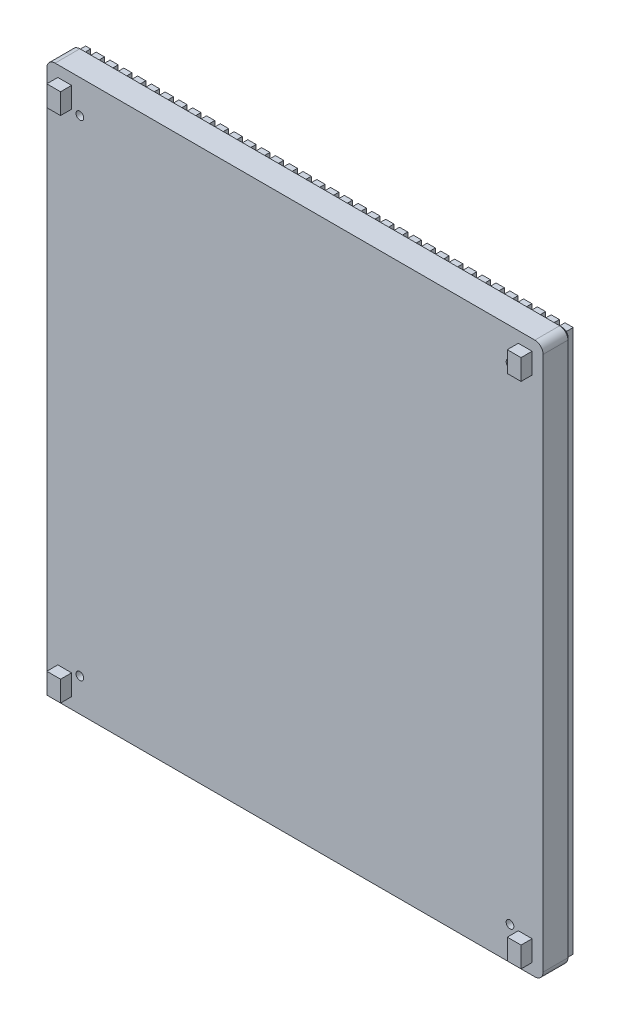
SolidWorks part; units mm, degrees
material "PLA"
ref_plane "Front Plane" through (0, 0, 0) normal (0, 0, 1) x (1, 0, 0)
ref_plane "Top Plane" through (0, 0, 0) normal (0, 1, 0) x (1, 0, 0)
ref_plane "Right Plane" through (0, 0, 0) normal (1, 0, 0) x (0, 0, -1)
sketch "Sketch1" plane through (0, 0, 0) normal (0, 0, 1) x (1, 0, 0)
  line L1 (-180, 200) -> (0, 200)
  line L2 (-180, 200) -> (-180, 0)
  line L3 (-180, 0) -> (0, 0)
  line L4 (0, 200) -> (0, 0)
  circle A0 centre (-168, 188) radius 1.4
  circle A1 centre (-12, 188) radius 1.4
  circle A2 centre (-12, 12) radius 1.4
  circle A3 centre (-168, 12) radius 1.4
  dimension "D3" = 2.8
  dimension "D4" = 2.8
  dimension "D5" = 2.8
  dimension "D6" = 2.8
  dimension "D9" = 12
  dimension "D10" = 12
  dimension "D11" = 12
  dimension "D12" = 12
  dimension "D13" = 12
  dimension "D14" = 12
  dimension "D1" = 200
  dimension "D2" = 180
  dimension "D7" = 12
  dimension "D8" = 12
extrude "Boss-Extrude1" add sketch "Sketch1" along normal blind 10
fillet "Fillet1" radius 3 4 edges at (0, 0, 5) (-180, 0, 5) (-180, 200, 5) (0, 200, 5)
chamfer "Chamfer1" distance 5 angle 40 4 edges at (-10.6, 12, 0) (-166.6, 12, 0) (-166.6, 188, 0) (-10.6, 188, 0)
chamfer "Chamfer2" distance 1 angle 45 8 edges at (-0.8787, 199.1213, 0) (-90, 200, 0) (-179.1213, 199.1213, 0) (-180, 100, 0) (-179.1213, 0.8787, 0) (0, 100, 0) (-0.8787, 0.8787, 0) (-90, 0, 0)
ref_plane "Plane1" through (-90, 0, 0) normal (1, 0, 0) x (0, 0, -1)
sketch "Sketch2" plane through (0, 0, 10) normal (0, 0, 1) x (1, 0, 0)
  line L1 (-176, 196) -> (-171.01, 196)
  line L2 (-176, 196) -> (-176, 188.51)
  line L3 (-176, 188.51) -> (-171.01, 188.51)
  line L4 (-171.01, 196) -> (-171.01, 188.51)
  line L6 (-3, 200) -> (-177, 200) construction
  line L7 (-180, 197) -> (-180, 3) construction
  point P8 (-171.01, 192.255)
  dimension "D1" = 4
  dimension "D2" = 4
  dimension "D3" = 7.49
  dimension "D4" = 4.99
extrude "Boss-Extrude2" add sketch "Sketch2" along normal blind 4
mirror "Mirror1" about plane through (-90, 0, 0) normal (1, 0, 0) of "Boss-Extrude2"
ref_plane "Plane2" through (0, 100, 0) normal (0, 1, 0) x (1, 0, 0)
mirror "Mirror2" about plane through (0, 100, 0) normal (0, 1, 0) of "Mirror1", "Boss-Extrude2"
sketch "Sketch3" plane through (0, 0, 0) normal (0, 0, -1) x (-1, 0, 0)
  line L0 (6.5858, 10.5872) -> (6.5858, 1.5858)
  line L1 (1.5858, 198.4142) -> (4.5858, 198.4142)
  line L2 (1.5858, 198.4142) -> (1.5858, 1.5858)
  line L3 (1.5858, 1.5858) -> (4.5858, 1.5858)
  line L4 (177, 199) -> (3, 199)
  line L5 (1, 197) -> (1, 3)
  line L6 (3, 1) -> (177, 1)
  line L7 (179, 3) -> (179, 197)
  line L8 (177, 199) -> (3, 199)
  line L9 (1, 197) -> (1, 3)
  line L10 (3, 1) -> (177, 1)
  line L11 (179, 3) -> (179, 197)
  line L12 (4.5858, 198.4142) -> (4.5858, 1.5858)
  line L13 (4.5858, 198.4142) -> (6.5858, 198.4142)
  line L14 (4.5858, 198.4142) -> (4.5858, 1.5858)
  line L15 (4.5858, 1.5858) -> (6.5858, 1.5858)
  line L16 (6.5858, 198.4142) -> (6.5858, 189.4128)
  line L17 (6.5858, 186.5872) -> (6.5858, 13.4128)
  line L18 (6.5858, 10.5872) -> (6.5858, 1.5858)
  line L19 (6.5858, 198.4142) -> (9.5858, 198.4142)
  line L20 (6.5858, 198.4142) -> (6.5858, 189.4128)
  line L21 (6.5858, 1.5858) -> (9.5858, 1.5858)
  line L22 (9.5858, 198.4142) -> (9.5858, 193.0479)
  line L23 (9.5858, 6.9521) -> (9.5858, 1.5858)
  line L24 (6.5858, 186.5872) -> (6.5858, 13.4128)
  line L25 (9.5858, 182.9521) -> (9.5858, 17.0479)
  line L26 (11.5858, 6.4199) -> (11.5858, 1.5858)
  line L27 (9.5858, 6.9521) -> (9.5858, 1.5858)
  line L28 (9.5858, 198.4142) -> (11.5858, 198.4142)
  line L29 (9.5858, 198.4142) -> (9.5858, 193.0479)
  line L30 (9.5858, 1.5858) -> (11.5858, 1.5858)
  line L31 (11.5858, 198.4142) -> (11.5858, 193.5801)
  line L32 (11.5858, 182.4199) -> (11.5858, 17.5801)
  line L33 (9.5858, 182.9521) -> (9.5858, 17.0479)
  line L34 (14.5858, 7.0378) -> (14.5858, 1.5858)
  line L35 (11.5858, 198.4142) -> (14.5858, 198.4142)
  line L36 (11.5858, 198.4142) -> (11.5858, 193.5801)
  line L37 (11.5858, 1.5858) -> (14.5858, 1.5858)
  line L38 (14.5858, 198.4142) -> (14.5858, 192.9622)
  line L39 (11.5858, 6.4199) -> (11.5858, 1.5858)
  line L40 (14.5858, 183.0378) -> (14.5858, 16.9622)
  line L41 (11.5858, 182.4199) -> (11.5858, 17.5801)
  line L42 (16.5858, 8.7937) -> (16.5858, 1.5858)
  line L43 (14.5858, 198.4142) -> (16.5858, 198.4142)
  line L44 (14.5858, 198.4142) -> (14.5858, 192.9622)
  line L45 (14.5858, 1.5858) -> (16.5858, 1.5858)
  line L46 (16.5858, 198.4142) -> (16.5858, 191.2063)
  line L47 (14.5858, 7.0378) -> (14.5858, 1.5858)
  line L48 (16.5858, 184.7937) -> (16.5858, 15.2063)
  line L49 (14.5858, 183.0378) -> (14.5858, 16.9622)
  line L50 (16.5858, 8.7937) -> (16.5858, 1.5858)
  line L51 (16.5858, 198.4142) -> (19.5858, 198.4142)
  line L52 (16.5858, 198.4142) -> (16.5858, 191.2063)
  line L53 (16.5858, 1.5858) -> (19.5858, 1.5858)
  line L54 (19.5858, 198.4142) -> (19.5858, 1.5858)
  line L55 (16.5858, 184.7937) -> (16.5858, 15.2063)
  circle A0 centre (168, 12) radius 5.5955 construction
  circle A1 centre (12, 12) radius 5.5955 construction
  circle A2 centre (168, 188) radius 5.5955 construction
  circle A3 centre (12, 188) radius 5.5955 construction
  arc A4 (3, 199) -> (1, 197) centre (3, 197) ccw
  arc A5 (1, 3) -> (3, 1) centre (3, 3) ccw
  arc A6 (177, 1) -> (179, 3) centre (177, 3) ccw
  arc A7 (179, 197) -> (177, 199) centre (177, 197) ccw
  arc A8 (3, 199) -> (1, 197) centre (3, 197) ccw
  arc A9 (1, 3) -> (3, 1) centre (3, 3) ccw
  arc A10 (177, 1) -> (179, 3) centre (177, 3) ccw
  arc A11 (179, 197) -> (177, 199) centre (177, 197) ccw
  circle A12 centre (168, 12) radius 5.5955
  circle A13 centre (12, 12) radius 5.5955
  circle A14 centre (168, 188) radius 5.5955
  circle A15 centre (12, 188) radius 5.5955
  circle M28 centre (12, 188) radius 5.5955
  circle M29 centre (12, 12) radius 5.5955
  dimension "D2" = 3
  dimension "D3" = 2
  dimension "D4" = 3
  dimension "D5" = 2
  dimension "D6" = 3
  dimension "D7" = 2
  dimension "D8" = 3
  dimension "D1" = 0
extrude "Boss-Extrude3" add sketch "Sketch3" along normal blind 2.5 contours L12 L1 L2 L3 | L25 L17 M28 M29 | L22 L19 L16 M28 | L40 L32 M28 M29 | L54 L51 L46 L48 L42 L53 M28 M29 | L38 L35 L31 M28 | L23 L0 L21 M29 | L26 L37 L34 M29
sketch "Sketch4" plane through (0, 0, 0) normal (0, 0, -1) x (-1, 0, 0)
  line L1 (19.5858, 198.4142) -> (21.5858, 198.4142)
  line L2 (19.5858, 198.4142) -> (19.5858, 1.5858)
  line L3 (19.5858, 1.5858) -> (21.5858, 1.5858)
  line L4 (21.5858, 198.4142) -> (21.5858, 1.5858)
  line L5 (21.5858, 1.5858) -> (24.5858, 1.5858)
  line L6 (21.5858, 1.5858) -> (21.5858, 198.4142)
  line L7 (21.5858, 198.4142) -> (24.5858, 198.4142)
  line L8 (24.5858, 1.5858) -> (24.5858, 198.4142)
  line L9 (24.5858, 198.4142) -> (26.5858, 198.4142)
  line L10 (24.5858, 198.4142) -> (24.5858, 1.5858)
  line L11 (24.5858, 1.5858) -> (26.5858, 1.5858)
  line L12 (26.5858, 198.4142) -> (26.5858, 1.5858)
  line L13 (26.5858, 1.5858) -> (29.5858, 1.5858)
  line L14 (26.5858, 1.5858) -> (26.5858, 198.4142)
  line L15 (26.5858, 198.4142) -> (29.5858, 198.4142)
  line L16 (29.5858, 1.5858) -> (29.5858, 198.4142)
  line L17 (29.5858, 198.4142) -> (31.5858, 198.4142)
  line L18 (29.5858, 198.4142) -> (29.5858, 1.5858)
  line L19 (29.5858, 1.5858) -> (31.5858, 1.5858)
  line L20 (31.5858, 198.4142) -> (31.5858, 1.5858)
  line L21 (31.5858, 1.5858) -> (34.5858, 1.5858)
  line L22 (31.5858, 1.5858) -> (31.5858, 198.4142)
  line L23 (31.5858, 198.4142) -> (34.5858, 198.4142)
  line L24 (34.5858, 1.5858) -> (34.5858, 198.4142)
  dimension "D1" = 2
  dimension "D2" = 3
  dimension "D3" = 2
  dimension "D4" = 3
  dimension "D5" = 2
  dimension "D6" = 3
extrude "Boss-Extrude5" add sketch "Sketch4" along normal blind 2.5 contours L5 L8 L7 L4 | L13 L16 L15 L12 | L21 L24 L23 L20
pattern_linear "LPattern2" count 13 spacing 10 along (-1, 0, 0) of "Boss-Extrude5"
sketch "Sketch5" plane through (0, 0, 0) normal (0, 0, -1) x (-1, 0, 0)
  line L0 (164.5858, 16.4331) -> (164.5858, 183.5669)
  line L1 (154.5858, 198.4142) -> (156.5858, 198.4142)
  line L2 (154.5858, 198.4142) -> (154.5858, 1.5858)
  line L3 (154.5858, 1.5858) -> (156.5858, 1.5858)
  line L4 (156.5858, 198.4142) -> (156.5858, 1.5858)
  line L5 (156.5858, 1.5858) -> (159.5858, 1.5858)
  line L6 (156.5858, 1.5858) -> (156.5858, 198.4142)
  line L7 (156.5858, 198.4142) -> (159.5858, 198.4142)
  line L8 (159.5858, 1.5858) -> (159.5858, 198.4142)
  line L9 (159.5858, 198.4142) -> (161.5858, 198.4142)
  line L10 (159.5858, 198.4142) -> (159.5858, 1.5858)
  line L11 (159.5858, 1.5858) -> (161.5858, 1.5858)
  line L12 (161.5858, 198.4142) -> (161.5858, 1.5858)
  line L13 (161.5858, 1.5858) -> (164.5858, 1.5858)
  line L14 (161.5858, 1.5858) -> (161.5858, 198.4142)
  line L15 (161.5858, 198.4142) -> (164.5858, 198.4142)
  line L16 (164.5858, 1.5858) -> (164.5858, 7.5669)
  line L17 (164.5858, 192.4331) -> (164.5858, 198.4142)
  line L18 (169.5858, 193.3661) -> (169.5858, 198.4142)
  line L19 (164.5858, 198.4142) -> (166.5858, 198.4142)
  line L20 (164.5858, 198.4142) -> (164.5858, 192.4331)
  line L21 (164.5858, 1.5858) -> (166.5858, 1.5858)
  line L22 (166.5858, 198.4142) -> (166.5858, 193.4138)
  line L23 (166.5858, 1.5858) -> (169.5858, 1.5858)
  line L24 (166.5858, 1.5858) -> (166.5858, 6.5862)
  line L25 (166.5858, 198.4142) -> (169.5858, 198.4142)
  line L26 (169.5858, 1.5858) -> (169.5858, 6.6339)
  line L27 (166.5858, 182.5862) -> (166.5858, 17.4138)
  line L28 (166.5858, 193.4138) -> (166.5858, 198.4142)
  line L29 (164.5858, 183.5669) -> (164.5858, 16.4331)
  line L30 (169.5858, 17.3661) -> (169.5858, 182.6339)
  line L31 (166.5858, 17.4138) -> (166.5858, 182.5862)
  line L32 (166.5858, 6.5862) -> (166.5858, 1.5858)
  line L33 (164.5858, 7.5669) -> (164.5858, 1.5858)
  line L34 (169.5858, 6.6339) -> (169.5858, 1.5858)
  line L35 (169.5858, 198.4142) -> (171.5858, 198.4142)
  line L36 (169.5858, 198.4142) -> (169.5858, 193.3661)
  line L37 (169.5858, 1.5858) -> (171.5858, 1.5858)
  line L38 (171.5858, 198.4142) -> (171.5858, 192.2955)
  line L39 (171.5858, 1.5858) -> (174.5858, 1.5858)
  line L40 (171.5858, 1.5858) -> (171.5858, 7.7045)
  line L41 (171.5858, 198.4142) -> (174.5858, 198.4142)
  line L42 (174.5858, 1.5858) -> (174.5858, 198.4142)
  line L43 (174.5858, 198.4142) -> (176.5858, 198.4142)
  line L44 (174.5858, 198.4142) -> (174.5858, 1.5858)
  line L45 (174.5858, 1.5858) -> (176.5858, 1.5858)
  line L46 (176.5858, 198.4142) -> (176.5858, 1.5858)
  line L47 (176.5858, 198.4142) -> (178.4142, 198.4142)
  line L48 (176.5858, 198.4142) -> (176.5858, 1.5858)
  line L49 (176.5858, 1.5858) -> (178.4142, 1.5858)
  line L50 (178.4142, 198.4142) -> (178.4142, 1.5858)
  line L51 (171.5858, 7.7045) -> (171.5858, 1.5858)
  line L52 (171.5858, 16.2955) -> (171.5858, 183.7045)
  line L53 (169.5858, 182.6339) -> (169.5858, 17.3661)
  line L54 (171.5858, 183.7045) -> (171.5858, 16.2955)
  line L55 (171.5858, 192.2955) -> (171.5858, 198.4142)
  circle A0 centre (168, 12) radius 5.5955 construction
  circle A1 centre (168, 188) radius 5.5955 construction
  circle A2 centre (168, 12) radius 5.5955
  circle A3 centre (168, 188) radius 5.5955
  arc A4 (177, 1) -> (179, 3) centre (177, 3) ccw construction
  dimension "D1" = 2
  dimension "D2" = 3
  dimension "D3" = 2
  dimension "D4" = 3
  dimension "D5" = 2
  dimension "D6" = 3
  dimension "D7" = 2
  dimension "D8" = 3
  dimension "D9" = 2
extrude "Boss-Extrude6" add sketch "Sketch5" along normal blind 2.5 contours L5 L8 L7 L4 | A3 L17 L15 L12 L13 L16 A2 L0 | A3 L18 L25 L22 | A3 L52 A2 L40 L39 L42 L41 L38 | L50 L47 L46 L49 | A3 L27 A2 L30 | A2 L24 L23 L26
